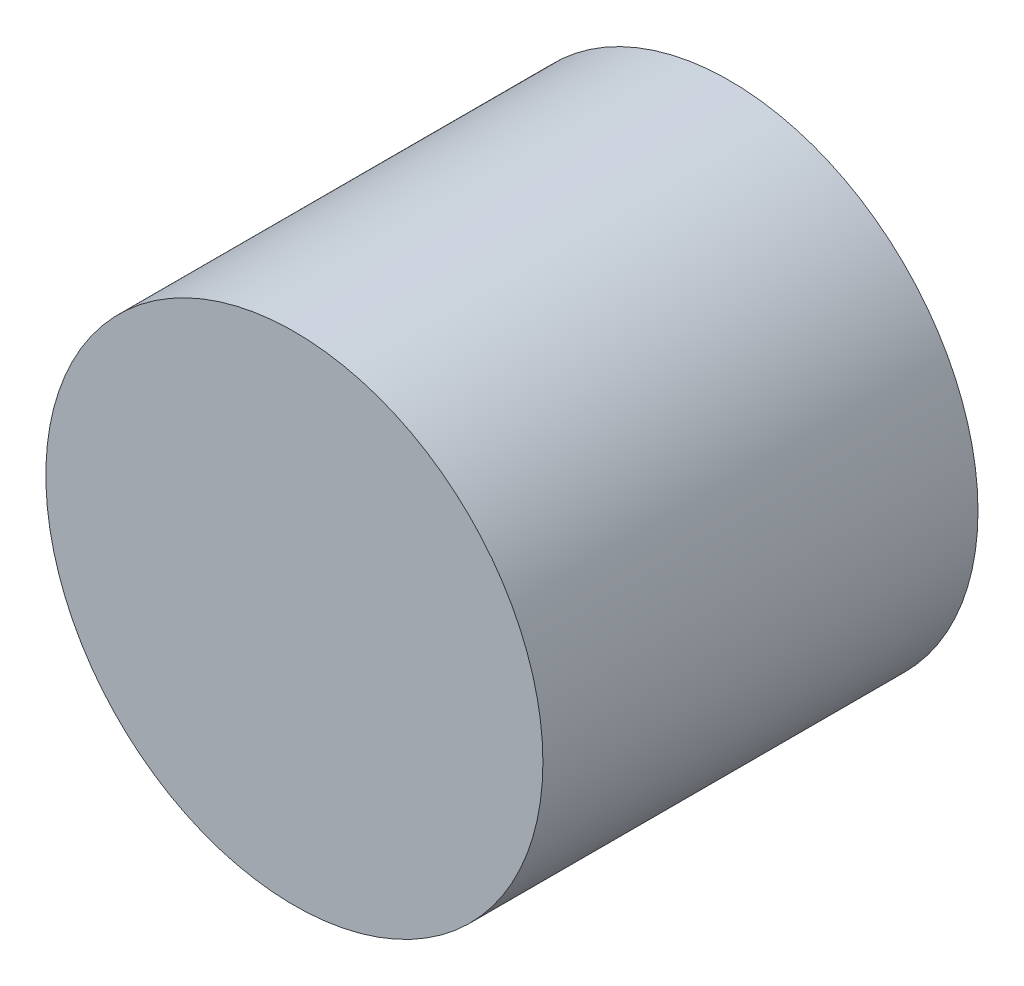
SolidWorks part; units mm, degrees
other "DetailItem1"
ref_plane "Front Plane" through (0, 0, 0) normal (0, 0, 1) x (1, 0, 0)
ref_plane "Top Plane" through (0, 0, 0) normal (0, 1, 0) x (1, 0, 0)
ref_plane "Right Plane" through (0, 0, 0) normal (1, 0, 0) x (0, 0, -1)
sketch "Sketch1" plane through (0, 0, 0) normal (0, 0, 1) x (1, 0, 0)
  circle A0 centre (0, 0) radius 7.98
  dimension "D1" = 15.96
extrude "Extrude1" add sketch "Sketch1" along normal blind 13.97
